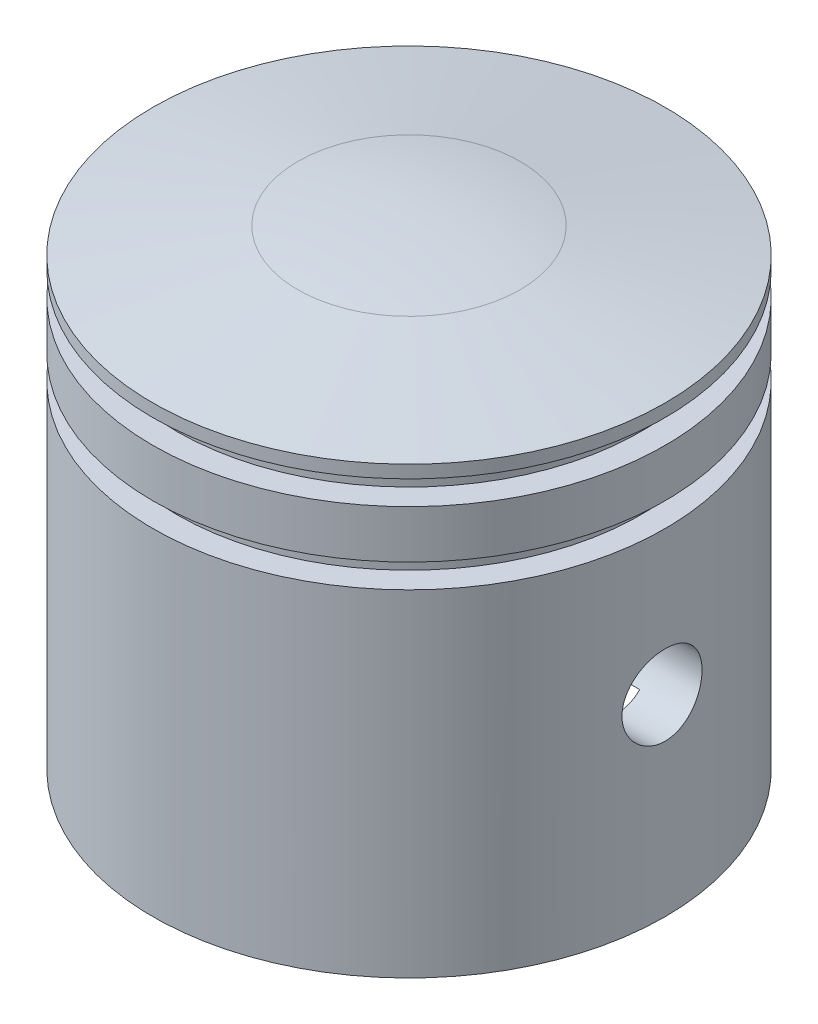
SolidWorks part; units mm, degrees
ref_plane "Front Plane" through (0, 0, 0) normal (0, 0, 1) x (1, 0, 0)
ref_plane "Top Plane" through (0, 0, 0) normal (0, 1, 0) x (1, 0, 0)
ref_plane "Right Plane" through (0, 0, 0) normal (1, 0, 0) x (0, 0, -1)
sketch "Sketch1" plane through (0, 0, 0) normal (0, 0, 1) x (1, 0, 0)
  line L0 (0, 0) -> (16, 0)
  line L1 (16, 0) -> (16, 27.7958)
  line L2 (16, 27.7958) -> (6.9459, 29.3923)
  line L3 (0, 30) -> (0, 0)
  line L4 (6.9459, 29.3923) -> (27.5171, 29.3923) construction
  arc A0 (6.9459, 29.3923) -> (0, 30) centre (0, -10) ccw
  point P7 (0, 0)
  dimension "D4" = 40
  dimension "D1" = 30
  dimension "D2" = 16
  dimension "D3" = 10
revolve "Revolve1" add sketch "Sketch1" angle 360 about L3
sketch "Sketch2" plane through (0, 0, 0) normal (0, 0, 1) x (1, 0, 0)
  line L0 (0, 0) -> (0, 28.7468) construction
  line L1 (-16, 0) -> (16, 0) construction
  line L2 (14.5, 27) -> (17.8844, 27)
  line L3 (14.5, 27) -> (14.5, 25.5)
  line L4 (14.5, 25.5) -> (17.8844, 25.5)
  line L5 (17.8844, 27) -> (17.8844, 25.5)
  line L6 (14.5, 22.5) -> (17.8844, 22.5)
  line L7 (14.5, 22.5) -> (14.5, 21)
  line L8 (14.5, 21) -> (17.8844, 21)
  line L9 (17.8844, 22.5) -> (17.8844, 21)
  dimension "D1" = 3
  dimension "D2" = 1.5
  dimension "D3" = 1.5
  dimension "D4" = 21
  dimension "D5" = 14.5
revolve "Cut-Revolve1" cut sketch "Sketch2" angle 360 about L0
sketch "Sketch3" plane through (0, 0, 0) normal (0, -1, 0) x (1, 0, 0)
  circle A0 centre (0, 0) radius 10
  dimension "D1" = 20
extrude "Cut-Extrude1" cut sketch "Sketch3" against normal blind 24
sketch "Sketch4" plane through (0, 0, 0) normal (0, -1, 0) x (1, 0, 0)
  circle A0 centre (0, 0) radius 13
  dimension "D1" = 26
extrude "Cut-Extrude2" cut sketch "Sketch4" against normal blind 10
sketch "Sketch5" plane through (0, 0, 0) normal (1, 0, 0) x (0, 0, -1)
  circle A1 centre (0, 12) radius 2.5
  point P2 (0, 0)
  dimension "D1" = 5
  dimension "D2" = 12
extrude "Cut-Extrude3" cut sketch "Sketch5" against normal through all both and the other way through all
